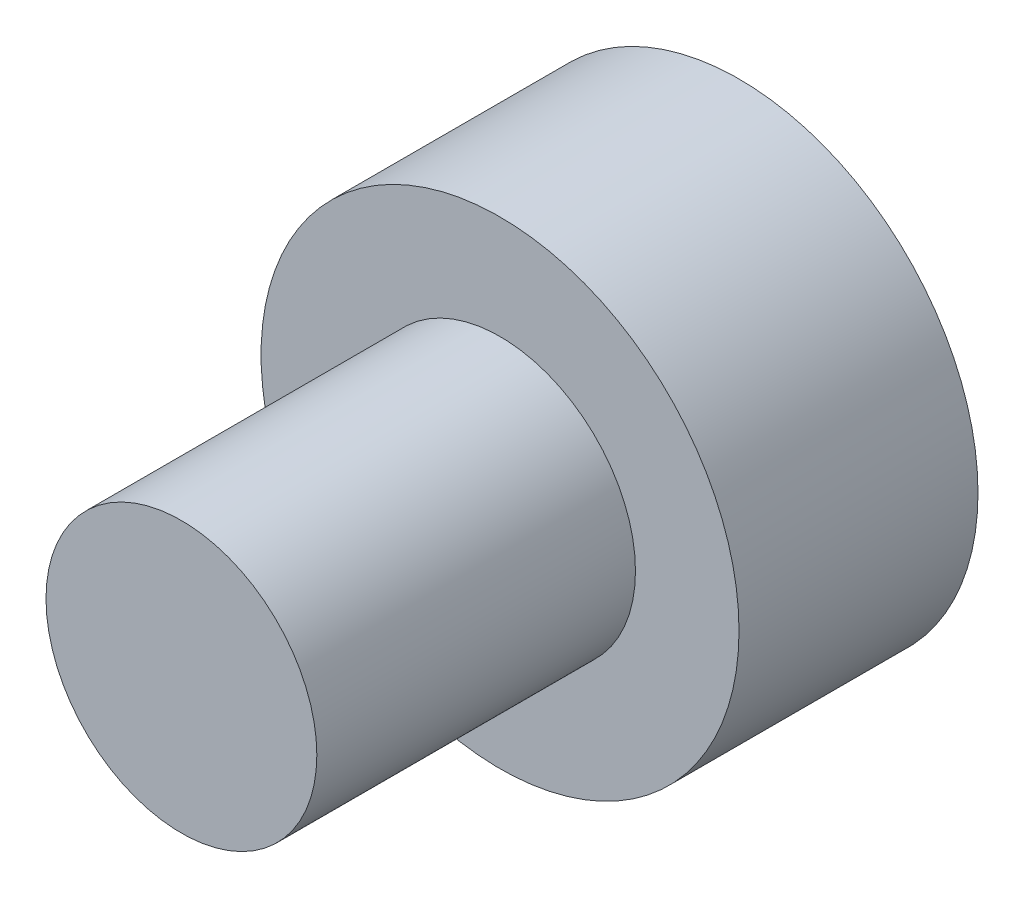
SolidWorks part; units mm, degrees
ref_plane "Front Plane" through (0, 0, 0) normal (0, 0, 1) x (1, 0, 0)
ref_plane "Top Plane" through (0, 0, 0) normal (0, 1, 0) x (1, 0, 0)
ref_plane "Right Plane" through (0, 0, 0) normal (1, 0, 0) x (0, 0, -1)
sketch "Sketch1" plane through (0, 0, 0) normal (0, 0, 1) x (1, 0, 0)
  circle A0 centre (0, 0) radius 3
extrude "Boss-Extrude1" add sketch "Sketch1" along normal blind 3
sketch "Sketch2" plane through (0, 0, 3) normal (0, 0, 1) x (1, 0, 0)
  circle A0 centre (0, 0) radius 1.7
extrude "Boss-Extrude2" add sketch "Sketch2" along normal blind 4 contours A0
sketch "Sketch3" plane through (0, 0, 0) normal (0, 0, -1) x (-1, 0, 0)
  circle A0 centre (0, 0) radius 2
extrude "Cut-Extrude1" cut sketch "Sketch3" against normal blind 0.2
